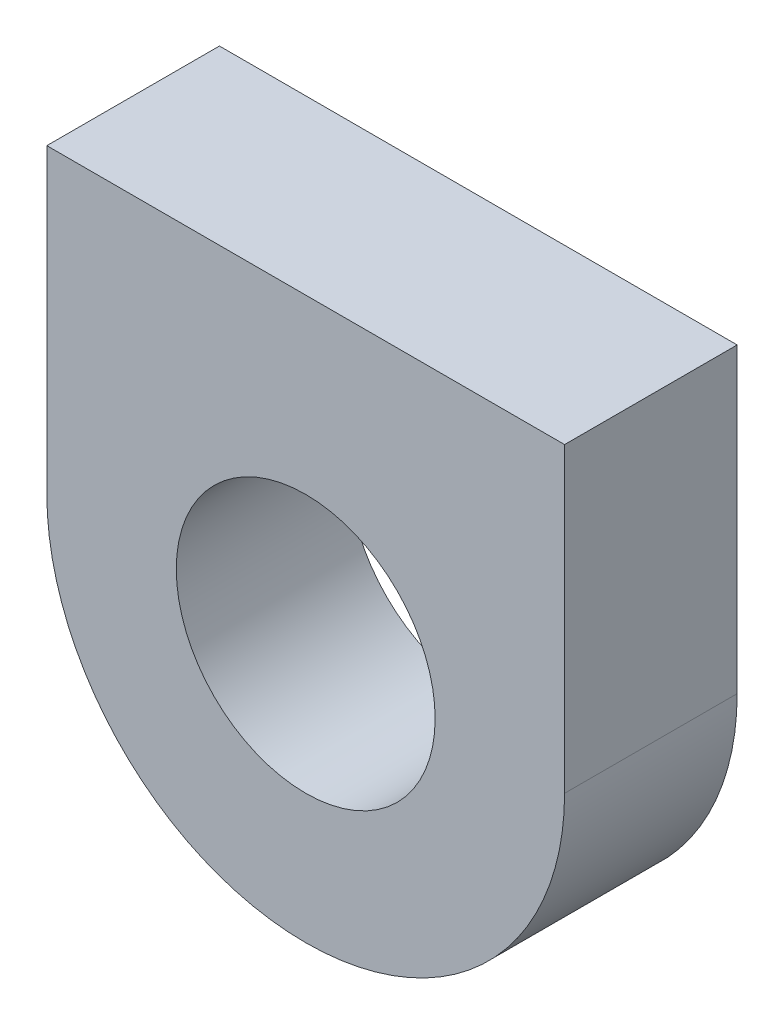
SolidWorks part; units mm, degrees
ref_plane "Front Plane" through (0, 0, 0) normal (0, 0, 1) x (1, 0, 0)
ref_plane "Top Plane" through (0, 0, 0) normal (0, 1, 0) x (1, 0, 0)
ref_plane "Right Plane" through (0, 0, 0) normal (1, 0, 0) x (0, 0, -1)
sketch "Sketch1" plane through (0, 0, 0) normal (0, 0, 1) x (1, 0, 0)
  line L0 (-30, 0) -> (-30, 35)
  line L1 (-30, 35) -> (30, 35)
  line L2 (30, 35) -> (30, 0)
  arc A0 (-30, 0) -> (30, 0) centre (0, 0) ccw
  circle A1 centre (0, 0) radius 15
  dimension "D1" = 60
  dimension "D2" = 30
  dimension "D3" = 35
extrude "Boss-Extrude1" add sketch "Sketch1" along normal mid plane 20
